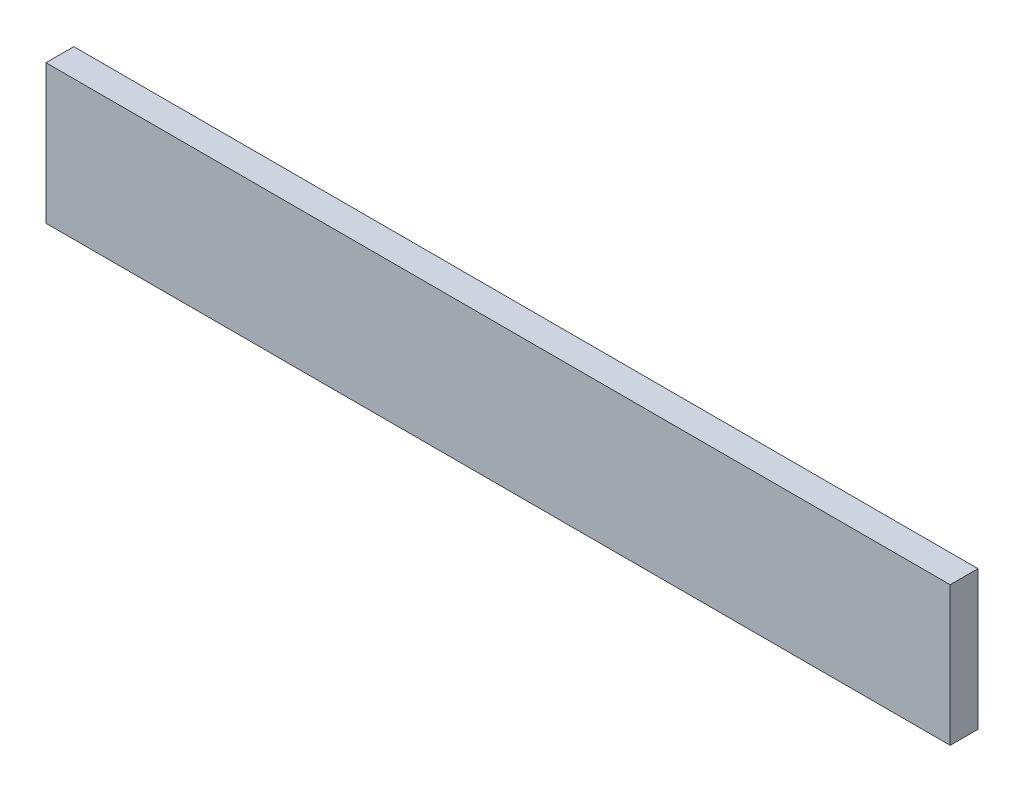
SolidWorks part; units mm, degrees
ref_plane "Front Plane" through (0, 0, 0) normal (0, 0, 1) x (1, 0, 0)
ref_plane "Top Plane" through (0, 0, 0) normal (0, 1, 0) x (1, 0, 0)
ref_plane "Right Plane" through (0, 0, 0) normal (1, 0, 0) x (0, 0, -1)
sketch "Sketch1" plane through (0, 0, 0) normal (0, 0, 1) x (1, 0, 0)
  line L1 (0, 0) -> (165.1, 0)
  line L2 (0, 0) -> (0, 25.4)
  line L3 (0, 25.4) -> (165.1, 25.4)
  line L4 (165.1, 0) -> (165.1, 25.4)
  dimension "D1" = 25.4
  dimension "D2" = 165.1
extrude "Boss-Extrude1" add sketch "Sketch1" along normal mid plane 5.08
equation "\"material\"= \"GMaterial@MotorizedPlatform.assembly\""
equation "\"D1@Boss-Extrude1\" = \"material\""
